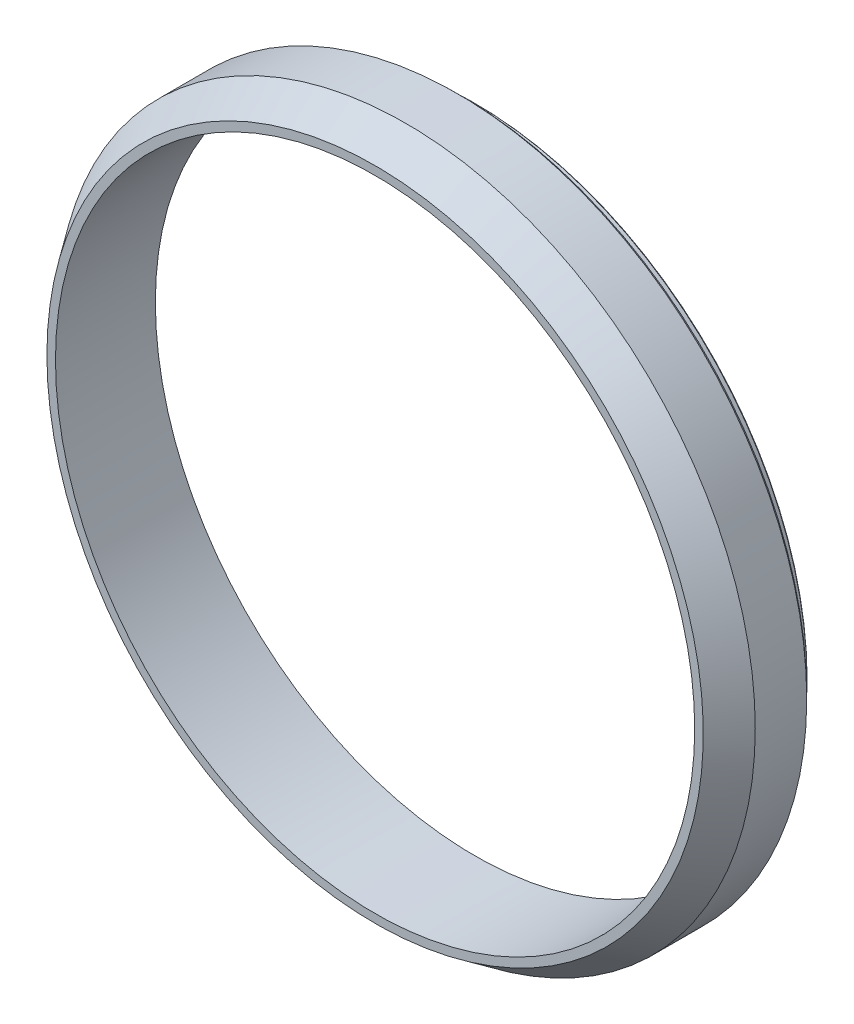
SolidWorks part; units mm, degrees
ref_plane "Front Plane" through (0, 0, 0) normal (0, 0, 1) x (1, 0, 0)
ref_plane "Top Plane" through (0, 0, 0) normal (0, 1, 0) x (1, 0, 0)
ref_plane "Right Plane" through (0, 0, 0) normal (1, 0, 0) x (0, 0, -1)
sketch "Sketch2" plane through (0, 0, 0) normal (0, 1, 0) x (1, 0, 0)
  line L0 (0, 51.2755) -> (0, -34.0986) construction
  line L1 (-58.3333, 0) -> (52.381, 0) construction
  line L2 (44.8, 14) -> (44.8, 0)
  line L3 (44.8, 0) -> (49, 0)
  line L4 (49, 0) -> (49, 12)
  line L5 (49, 12) -> (46.8, 12)
  line L6 (46.8, 12) -> (46.8, 14)
  line L7 (46.8, 14) -> (44.8, 14)
  dimension "D1" = 46.8
  dimension "D2" = 2
  dimension "D3" = 49
  dimension "D4" = 14
  dimension "D5" = 12
revolve "Revolve1" add sketch "Sketch2" angle 360 about L0
chamfer "Chamfer1" distance 0.25 angle 45 1 edges at (-46.8, 0, -14)
chamfer "Chamfer2" distance 0.5 angle 45 1 edges at (-49, 0, -12)
chamfer "Chamfer3" distance 3 angle 55 1 edges at (-49, 0, 0)
